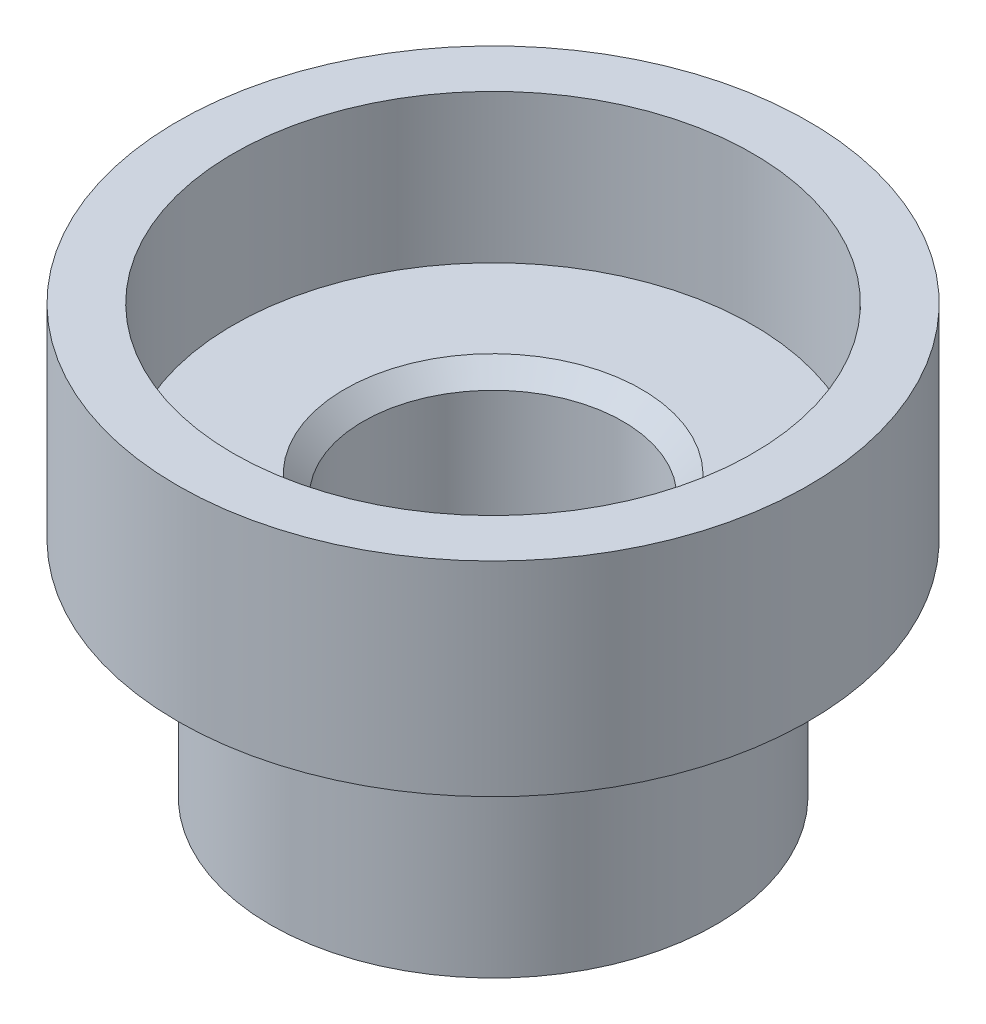
SolidWorks part; units mm, degrees
ref_plane "Front Plane" through (0, 0, 0) normal (0, 0, 1) x (1, 0, 0)
ref_plane "Top Plane" through (0, 0, 0) normal (0, 1, 0) x (1, 0, 0)
ref_plane "Right Plane" through (0, 0, 0) normal (1, 0, 0) x (0, 0, -1)
ref_plane "Plane1" through (0, 0, 0) normal (0, 0, -1) x (-1, 0, 0)
sketch "Sketch1" plane through (0, 0, 0) normal (0, 0, -1) x (-1, 0, 0)
  line L0 (-2.4, -4.6) -> (-1.4, -4.6)
  line L1 (-1.4, -4.6) -> (-1.4, -1.8)
  line L2 (-1.4, -1.8) -> (-1.6, -1.6)
  line L3 (-1.6, -1.6) -> (-2.8, -1.6)
  line L4 (-2.8, -1.6) -> (-2.8, 0)
  line L5 (-2.8, 0) -> (-3.4, 0)
  line L6 (-3.4, 0) -> (-3.4, -2.2)
  line L7 (-3.4, -2.2) -> (-2.6, -2.2)
  line L8 (-2.4, -2.4) -> (-2.4, -4.6)
  line L9 (0, -4.6) -> (0, 0) construction
  arc A0 (-2.6, -2.2) -> (-2.4, -2.4) centre (-2.6, -2.4) cw
revolve "Revolve1" add sketch "Sketch1" angle 360 about L9
